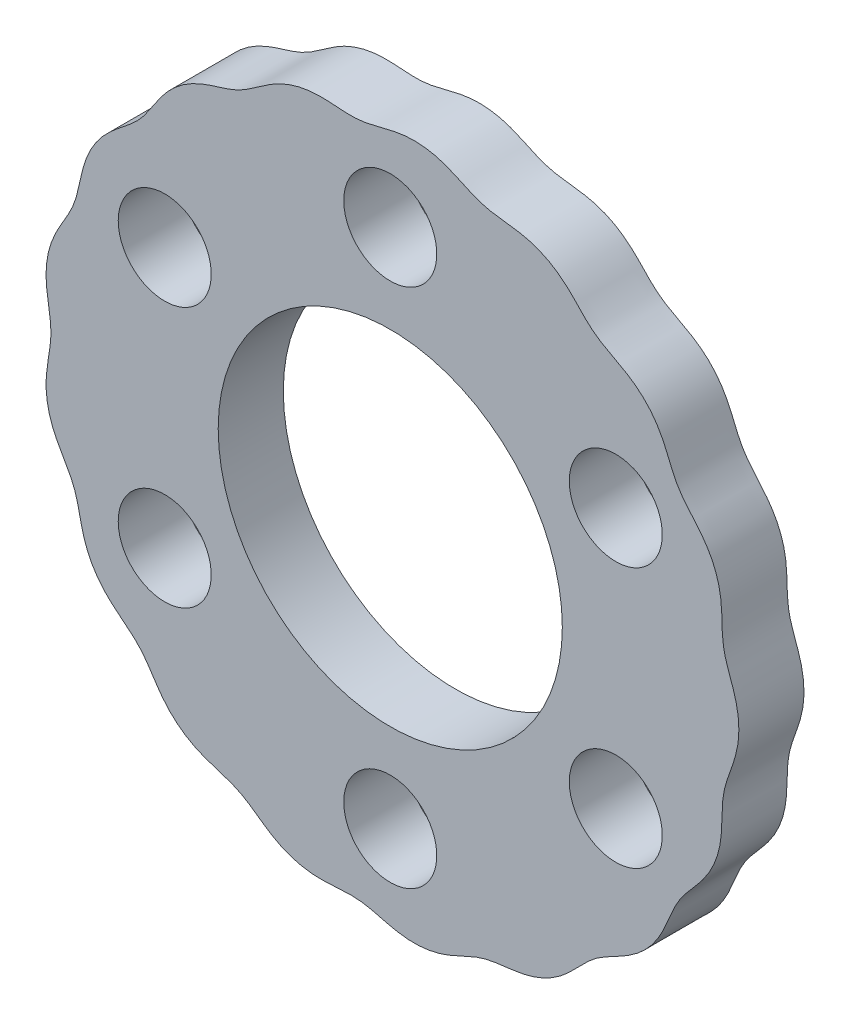
SolidWorks part; units mm, degrees
ref_plane "Front Plane" through (0, 0, 0) normal (0, 0, 1) x (1, 0, 0)
ref_plane "Top Plane" through (0, 0, 0) normal (0, 1, 0) x (1, 0, 0)
ref_plane "Right Plane" through (0, 0, 0) normal (1, 0, 0) x (0, 0, -1)
curve "Curve2"
  spline degree 3 poles (37.4783, -0.2259, 0) (37.4808, 0, 0) (37.4783, 0.2259, 0) (37.4707, 0.4525, 0) (37.4578, 0.6808, 0) (37.4392, 0.9112, 0) (37.4148, 1.1439, 0) (37.3841, 1.3792, 0) (37.347, 1.6168, 0) (37.3035, 1.8564, 0) (37.2536, 2.0975, 0) (37.1976, 2.3394, 0) (37.136, 2.5815, 0) (37.0693, 2.8232, 0) (36.9981, 3.0638, 0) (36.9231, 3.303, 0) (36.8453, 3.5401, 0) (36.7653, 3.7749, 0) (36.6841, 4.007, 0) (36.6025, 4.2364, 0) (36.5213, 4.463, 0) (36.4413, 4.6868, 0) (36.3632, 4.9078, 0) (36.2878, 5.1264, 0) (36.2156, 5.3428, 0) (36.1471, 5.5573, 0) (36.0829, 5.7702, 0) (36.0234, 5.9821, 0) (35.9687, 6.1933, 0) (35.9191, 6.4044, 0) (35.8748, 6.6158, 0) (35.8356, 6.8279, 0) (35.8015, 7.0413, 0) (35.7723, 7.2564, 0) (35.7478, 7.4735, 0) (35.7275, 7.693, 0) (35.7111, 7.9153, 0) (35.6979, 8.1406, 0) (35.6875, 8.369, 0) (35.6793, 8.6006, 0) (35.6724, 8.8355, 0) (35.6662, 9.0736, 0) (35.6601, 9.3147, 0) (35.6531, 9.5586, 0) (35.6447, 9.8048, 0) (35.634, 10.0529, 0) (35.6203, 10.3023, 0) (35.6031, 10.5525, 0) (35.5818, 10.8025, 0) (35.5559, 11.0518, 0) (35.525, 11.2995, 0) (35.4889, 11.5448, 0) (35.4474, 11.787, 0) (35.4005, 12.0254, 0) (35.3483, 12.2596, 0) (35.291, 12.4893, 0) (35.2289, 12.7144, 0) (35.1622, 12.9351, 0) (35.091, 13.152, 0) (35.0154, 13.3656, 0) (34.9354, 13.5768, 0) (34.8506, 13.7862, 0) (34.7607, 13.9947, 0) (34.6651, 14.2029, 0) (34.5635, 14.411, 0) (34.4554, 14.6192, 0) (34.3406, 14.8275, 0) (34.219, 15.0357, 0) (34.0907, 15.2432, 0) (33.956, 15.4497, 0) (33.8155, 15.6548, 0) (33.6697, 15.8579, 0) (33.5194, 16.0587, 0) (33.3655, 16.257, 0) (33.2088, 16.4524, 0) (33.0503, 16.6448, 0) (32.8908, 16.8344, 0) (32.7313, 17.021, 0) (32.5725, 17.205, 0) (32.4153, 17.3865, 0) (32.2603, 17.5659, 0) (32.1082, 17.7436, 0) (31.9595, 17.9199, 0) (31.8147, 18.0955, 0) (31.6742, 18.2708, 0) (31.5382, 18.4462, 0) (31.407, 18.6225, 0) (31.2806, 18.8, 0) (31.1589, 18.9792, 0) (31.042, 19.1607, 0) (30.9296, 19.3449, 0) (30.8215, 19.5321, 0) (30.7173, 19.7227, 0) (30.6165, 19.9169, 0) (30.5188, 20.115, 0) (30.4236, 20.3171, 0) (30.3303, 20.5231, 0) (30.2383, 20.733, 0) (30.1469, 20.9466, 0) (30.0556, 21.1638, 0) (29.9637, 21.3841, 0) (29.8706, 21.6072, 0) (29.7757, 21.8324, 0) (29.6784, 22.0591, 0) (29.5782, 22.2867, 0) (29.4748, 22.5143, 0) (29.3678, 22.7411, 0) (29.2569, 22.9663, 0) (29.1419, 23.1889, 0) (29.0229, 23.408, 0) (28.8999, 23.6228, 0) (28.7731, 23.8327, 0) (28.6426, 24.0371, 0) (28.5088, 24.2356, 0) (28.3719, 24.428, 0) (28.2321, 24.6144, 0) (28.0897, 24.7952, 0) (27.9445, 24.9709, 0) (27.7963, 25.142, 0) (27.6448, 25.3093, 0) (27.4893, 25.4735, 0) (27.3293, 25.635, 0) (27.164, 25.7942, 0) (26.9931, 25.9512, 0) (26.816, 26.1059, 0) (26.6325, 26.2582, 0) (26.4429, 26.4079, 0) (26.2472, 26.5545, 0) (26.0461, 26.6978, 0) (25.8402, 26.8376, 0) (25.6302, 26.9737, 0) (25.417, 27.106, 0) (25.2016, 27.2346, 0) (24.9847, 27.3596, 0) (24.7673, 27.4812, 0) (24.5503, 27.5998, 0) (24.3343, 27.7158, 0) (24.1202, 27.8297, 0) (23.9084, 27.9419, 0) (23.6997, 28.053, 0) (23.4943, 28.1637, 0) (23.2926, 28.2745, 0) (23.0949, 28.3861, 0) (22.9013, 28.4991, 0) (22.7119, 28.614, 0) (22.5265, 28.7314, 0) (22.3452, 28.8518, 0) (22.1677, 28.9756, 0) (21.9937, 29.1033, 0) (21.8229, 29.2352, 0) (21.6549, 29.3715, 0) (21.4892, 29.5124, 0) (21.3254, 29.658, 0) (21.163, 29.8082, 0) (21.0013, 29.963, 0) (20.8399, 30.1221, 0) (20.6781, 30.2853, 0) (20.5156, 30.4522, 0) (20.3517, 30.6222, 0) (20.1861, 30.7949, 0) (20.0183, 30.9695, 0) (19.848, 31.1454, 0) (19.6748, 31.3217, 0) (19.4987, 31.4976, 0) (19.3195, 31.6722, 0) (19.1372, 31.8446, 0) (18.9519, 32.0138, 0) (18.7639, 32.1791, 0) (18.5734, 32.3395, 0) (18.3807, 32.4944, 0) (18.1863, 32.6432, 0) (17.9906, 32.7855, 0) (17.794, 32.921, 0) (17.5967, 33.0498, 0) (17.399, 33.172, 0) (17.2008, 33.2881, 0) (17.0018, 33.3984, 0) (16.8015, 33.5036, 0) (16.5993, 33.6041, 0) (16.3945, 33.7003, 0) (16.1863, 33.7924, 0) (15.974, 33.8804, 0) (15.757, 33.9642, 0) (15.5351, 34.0438, 0) (15.3081, 34.1187, 0) (15.0764, 34.1889, 0) (14.8403, 34.2541, 0) (14.6003, 34.3142, 0) (14.3573, 34.3692, 0) (14.112, 34.4194, 0) (13.8652, 34.465, 0) (13.6178, 34.5064, 0) (13.3705, 34.544, 0) (13.1241, 34.5783, 0) (12.8791, 34.6101, 0) (12.6363, 34.64, 0) (12.3959, 34.6686, 0) (12.1585, 34.6967, 0) (11.9243, 34.725, 0) (11.6934, 34.7542, 0) (11.4659, 34.7851, 0) (11.2418, 34.8181, 0) (11.021, 34.8541, 0) (10.8034, 34.8934, 0) (10.5887, 34.9367, 0) (10.3766, 34.9842, 0) (10.1667, 35.0364, 0) (9.9586, 35.0935, 0) (9.7519, 35.1557, 0) (9.5461, 35.223, 0) (9.3408, 35.2955, 0) (9.1354, 35.3729, 0) (8.9295, 35.4551, 0) (8.7226, 35.5418, 0) (8.5143, 35.6326, 0) (8.3042, 35.7269, 0) (8.092, 35.8243, 0) (7.8773, 35.924, 0) (7.6601, 36.0254, 0) (7.44, 36.1277, 0) (7.2171, 36.2302, 0) (6.9915, 36.3318, 0) (6.7633, 36.4319, 0) (6.5327, 36.5295, 0) (6.3002, 36.6237, 0) (6.066, 36.7138, 0) (5.8308, 36.7991, 0) (5.5952, 36.8788, 0) (5.3596, 36.9526, 0) (5.1248, 37.0199, 0) (4.8911, 37.0807, 0) (4.6591, 37.1349, 0) (4.429, 37.1826, 0) (4.2008, 37.2241, 0) (3.9743, 37.2597, 0) (3.7491, 37.2898, 0) (3.5244, 37.3146, 0) (3.2995, 37.3344, 0) (3.0735, 37.3492, 0) (2.8457, 37.3589, 0) (2.6154, 37.3634, 0) (2.3823, 37.3622, 0) (2.1461, 37.3551, 0) (1.9069, 37.3419, 0) (1.665, 37.3225, 0) (1.4209, 37.2969, 0) (1.1753, 37.2652, 0) (0.9286, 37.2278, 0) (0.6818, 37.1851, 0) (0.4353, 37.1377, 0) (0.1899, 37.0862, 0) (-0.054, 37.0314, 0) (-0.2958, 36.974, 0) (-0.5352, 36.9149, 0) (-0.772, 36.8549, 0) (-1.0059, 36.7949, 0) (-1.237, 36.7355, 0) (-1.4651, 36.6776, 0) (-1.6905, 36.6218, 0) (-1.9134, 36.569, 0) (-2.1339, 36.5195, 0) (-2.3524, 36.474, 0) (-2.5692, 36.4329, 0) (-2.7849, 36.3965, 0) (-2.9998, 36.3651, 0) (-3.2143, 36.3389, 0) (-3.4291, 36.3179, 0) (-3.6444, 36.3021, 0) (-3.8608, 36.2914, 0) (-4.0788, 36.2857, 0) (-4.2986, 36.2845, 0) (-4.5207, 36.2874, 0) (-4.7454, 36.2942, 0) (-4.9729, 36.3041, 0) (-5.2035, 36.3165, 0) (-5.4371, 36.331, 0) (-5.6738, 36.3466, 0) (-5.9136, 36.3627, 0) (-6.1563, 36.3785, 0) (-6.4015, 36.3932, 0) (-6.649, 36.4062, 0) (-6.8982, 36.4165, 0) (-7.1486, 36.4236, 0) (-7.3996, 36.4267, 0) (-7.6504, 36.4253, 0) (-7.9003, 36.4189, 0) (-8.1485, 36.4072, 0) (-8.3943, 36.3899, 0) (-8.637, 36.3669, 0) (-8.8762, 36.3382, 0) (-9.1114, 36.3039, 0) (-9.3424, 36.2644, 0) (-9.5695, 36.2197, 0) (-9.793, 36.1703, 0) (-10.0134, 36.1161, 0) (-10.2316, 36.0573, 0) (-10.4482, 35.9936, 0) (-10.6642, 35.9249, 0) (-10.8802, 35.8507, 0) (-11.0966, 35.7705, 0) (-11.3137, 35.684, 0) (-11.5316, 35.5909, 0) (-11.7499, 35.491, 0) (-11.9684, 35.3844, 0) (-12.1867, 35.2712, 0) (-12.4042, 35.1519, 0) (-12.6204, 35.027, 0) (-12.8348, 34.8971, 0) (-13.0471, 34.7632, 0) (-13.2569, 34.626, 0) (-13.464, 34.4865, 0) (-13.6682, 34.3454, 0) (-13.8697, 34.2038, 0) (-14.0683, 34.0624, 0) (-14.2643, 33.9221, 0) (-14.4578, 33.7837, 0) (-14.6493, 33.6478, 0) (-14.8391, 33.515, 0) (-15.0276, 33.3859, 0) (-15.2152, 33.2608, 0) (-15.4025, 33.1403, 0) (-15.5899, 33.0244, 0) (-15.778, 32.9135, 0) (-15.9673, 32.8074, 0) (-16.1582, 32.7063, 0) (-16.3513, 32.61, 0) (-16.5469, 32.5183, 0) (-16.7454, 32.4309, 0) (-16.9471, 32.3475, 0) (-17.1523, 32.2675, 0) (-17.3611, 32.1906, 0) (-17.5737, 32.116, 0) (-17.7901, 32.0434, 0) (-18.0102, 31.9719, 0) (-18.2339, 31.901, 0) (-18.4609, 31.83, 0) (-18.6908, 31.7582, 0) (-18.9232, 31.685, 0) (-19.1575, 31.6097, 0) (-19.3931, 31.5319, 0) (-19.6292, 31.4509, 0) (-19.8652, 31.3664, 0) (-20.1001, 31.2779, 0) (-20.333, 31.1853, 0) (-20.5632, 31.0883, 0) (-20.7897, 30.9869, 0) (-21.0118, 30.8812, 0) (-21.229, 30.7714, 0) (-21.4406, 30.6575, 0) (-21.6465, 30.54, 0) (-21.8467, 30.419, 0) (-22.0414, 30.2948, 0) (-22.231, 30.1674, 0) (-22.4163, 30.0367, 0) (-22.5978, 29.9023, 0) (-22.7764, 29.764, 0) (-22.9526, 29.621, 0) (-23.1268, 29.4728, 0) (-23.2994, 29.3188, 0) (-23.4703, 29.1586, 0) (-23.6395, 28.992, 0) (-23.8066, 28.8188, 0) (-23.9715, 28.6393, 0) (-24.1336, 28.4539, 0) (-24.2927, 28.2632, 0) (-24.4486, 28.0679, 0) (-24.601, 27.8688, 0) (-24.75, 27.6668, 0) (-24.8955, 27.4628, 0) (-25.0376, 27.2577, 0) (-25.1766, 27.0524, 0) (-25.3127, 26.8478, 0) (-25.4465, 26.6445, 0) (-25.5782, 26.4433, 0) (-25.7085, 26.2448, 0) (-25.8378, 26.0494, 0) (-25.9668, 25.8577, 0) (-26.096, 25.67, 0) (-26.226, 25.4864, 0) (-26.3573, 25.307, 0) (-26.4907, 25.1321, 0) (-26.6264, 24.9614, 0) (-26.7652, 24.7949, 0) (-26.9073, 24.6323, 0) (-27.0533, 24.4734, 0) (-27.2032, 24.3178, 0) (-27.3575, 24.1651, 0) (-27.5163, 24.0148, 0) (-27.6795, 23.8664, 0) (-27.8473, 23.7194, 0) (-28.0193, 23.5732, 0) (-28.1956, 23.4273, 0) (-28.3757, 23.281, 0) (-28.5592, 23.1339, 0) (-28.7457, 22.9854, 0) (-28.9345, 22.8351, 0) (-29.125, 22.6824, 0) (-29.3164, 22.5271, 0) (-29.5079, 22.3689, 0) (-29.6987, 22.2075, 0) (-29.8878, 22.0429, 0) (-30.0743, 21.875, 0) (-30.2574, 21.7039, 0) (-30.4362, 21.5298, 0) (-30.6098, 21.353, 0) (-30.7777, 21.1738, 0) (-30.9394, 20.9925, 0) (-31.0944, 20.8097, 0) (-31.2428, 20.6255, 0) (-31.3846, 20.4402, 0) (-31.5202, 20.2539, 0) (-31.6501, 20.0663, 0) (-31.7747, 19.8772, 0) (-31.8947, 19.6859, 0) (-32.0105, 19.4918, 0) (-32.1225, 19.2942, 0) (-32.2308, 19.0922, 0) (-32.3354, 18.8854, 0) (-32.4363, 18.6734, 0) (-32.5331, 18.4559, 0) (-32.6256, 18.2331, 0) (-32.7136, 18.0054, 0) (-32.797, 17.7732, 0) (-32.8757, 17.5373, 0) (-32.9496, 17.2983, 0) (-33.0191, 17.0573, 0) (-33.0843, 16.815, 0) (-33.1456, 16.5722, 0) (-33.2035, 16.3297, 0) (-33.2584, 16.0883, 0) (-33.3111, 15.8486, 0) (-33.3622, 15.6112, 0) (-33.4122, 15.3765, 0) (-33.462, 15.1449, 0) (-33.5121, 14.9167, 0) (-33.5634, 14.6919, 0) (-33.6163, 14.4708, 0) (-33.6717, 14.2533, 0) (-33.73, 14.0392, 0) (-33.7917, 13.8285, 0) (-33.8574, 13.6208, 0) (-33.9274, 13.4159, 0) (-34.0021, 13.2133, 0) (-34.0816, 13.0127, 0) (-34.1662, 12.8137, 0) (-34.2557, 12.6157, 0) (-34.3503, 12.4183, 0) (-34.4498, 12.2209, 0) (-34.5539, 12.0231, 0) (-34.6623, 11.8244, 0) (-34.7746, 11.6244, 0) (-34.8902, 11.4227, 0) (-35.0087, 11.2188, 0) (-35.1292, 11.0125, 0) (-35.2511, 10.8037, 0) (-35.3737, 10.592, 0) (-35.496, 10.3776, 0) (-35.6171, 10.1604, 0) (-35.7363, 9.9405, 0) (-35.8526, 9.7183, 0) (-35.9652, 9.494, 0) (-36.0733, 9.268, 0) (-36.1761, 9.041, 0) (-36.2731, 8.8133, 0) (-36.3637, 8.5856, 0) (-36.4478, 8.3583, 0) (-36.5252, 8.132, 0) (-36.5958, 7.9069, 0) (-36.66, 7.6831, 0) (-36.7181, 7.4605, 0) (-36.7704, 7.2389, 0) (-36.8174, 7.0175, 0) (-36.8593, 6.7956, 0) (-36.8963, 6.5725, 0) (-36.9285, 6.3474, 0) (-36.9556, 6.1194, 0) (-36.9776, 5.8882, 0) (-36.994, 5.6534, 0) (-37.0047, 5.415, 0) (-37.0094, 5.1733, 0) (-37.0082, 4.9286, 0) (-37.001, 4.6816, 0) (-36.9882, 4.433, 0) (-36.9699, 4.1834, 0) (-36.9468, 3.9335, 0) (-36.9193, 3.6841, 0) (-36.8882, 3.4358, 0) (-36.8541, 3.1891, 0) (-36.8178, 2.9446, 0) (-36.7802, 2.7025, 0) (-36.7419, 2.4632, 0) (-36.7039, 2.2268, 0) (-36.6669, 1.9934, 0) (-36.6316, 1.7629, 0) (-36.5986, 1.5354, 0) (-36.5687, 1.3105, 0) (-36.5424, 1.0881, 0) (-36.5202, 0.8678, 0) (-36.5025, 0.6492, 0) (-36.4896, 0.4321, 0) (-36.4818, 0.2158, 0) (-36.4791, 0, 0) (-36.4818, -0.2158, 0) (-36.4896, -0.4321, 0) (-36.5025, -0.6492, 0) (-36.5202, -0.8678, 0) (-36.5424, -1.0881, 0) (-36.5687, -1.3105, 0) (-36.5986, -1.5354, 0) (-36.6316, -1.7629, 0) (-36.6669, -1.9934, 0) (-36.7039, -2.2268, 0) (-36.7419, -2.4632, 0) (-36.7802, -2.7025, 0) (-36.8178, -2.9446, 0) (-36.8541, -3.1891, 0) (-36.8882, -3.4358, 0) (-36.9193, -3.6841, 0) (-36.9468, -3.9335, 0) (-36.9699, -4.1834, 0) (-36.9882, -4.433, 0) (-37.001, -4.6816, 0) (-37.0082, -4.9286, 0) (-37.0094, -5.1733, 0) (-37.0047, -5.415, 0) (-36.994, -5.6534, 0) (-36.9776, -5.8882, 0) (-36.9556, -6.1194, 0) (-36.9285, -6.3474, 0) (-36.8963, -6.5725, 0) (-36.8593, -6.7956, 0) (-36.8174, -7.0175, 0) (-36.7704, -7.2389, 0) (-36.7181, -7.4605, 0) (-36.66, -7.6831, 0) (-36.5958, -7.9069, 0) (-36.5252, -8.132, 0) (-36.4478, -8.3583, 0) (-36.3637, -8.5856, 0) (-36.2731, -8.8133, 0) (-36.1761, -9.041, 0) (-36.0733, -9.268, 0) (-35.9652, -9.494, 0) (-35.8526, -9.7183, 0) (-35.7363, -9.9405, 0) (-35.6171, -10.1604, 0) (-35.496, -10.3776, 0) (-35.3737, -10.592, 0) (-35.2511, -10.8037, 0) (-35.1292, -11.0125, 0) (-35.0087, -11.2188, 0) (-34.8902, -11.4227, 0) (-34.7746, -11.6244, 0) (-34.6623, -11.8244, 0) (-34.5539, -12.0231, 0) (-34.4498, -12.2209, 0) (-34.3503, -12.4183, 0) (-34.2557, -12.6157, 0) (-34.1662, -12.8137, 0) (-34.0816, -13.0127, 0) (-34.0021, -13.2133, 0) (-33.9274, -13.4159, 0) (-33.8574, -13.6208, 0) (-33.7917, -13.8285, 0) (-33.73, -14.0392, 0) (-33.6717, -14.2533, 0) (-33.6163, -14.4708, 0) (-33.5634, -14.6919, 0) (-33.5121, -14.9167, 0) (-33.462, -15.1449, 0) (-33.4122, -15.3765, 0) (-33.3622, -15.6112, 0) (-33.3111, -15.8486, 0) (-33.2584, -16.0883, 0) (-33.2035, -16.3297, 0) (-33.1456, -16.5722, 0) (-33.0843, -16.815, 0) (-33.0191, -17.0573, 0) (-32.9496, -17.2983, 0) (-32.8757, -17.5373, 0) (-32.797, -17.7732, 0) (-32.7136, -18.0054, 0) (-32.6256, -18.2331, 0) (-32.5331, -18.4559, 0) (-32.4363, -18.6734, 0) (-32.3354, -18.8854, 0) (-32.2308, -19.0922, 0) (-32.1225, -19.2942, 0) (-32.0105, -19.4918, 0) (-31.8947, -19.6859, 0) (-31.7747, -19.8772, 0) (-31.6501, -20.0663, 0) (-31.5202, -20.2539, 0) (-31.3846, -20.4402, 0) (-31.2428, -20.6255, 0) (-31.0944, -20.8097, 0) (-30.9394, -20.9925, 0) (-30.7777, -21.1738, 0) (-30.6098, -21.353, 0) (-30.4362, -21.5298, 0) (-30.2574, -21.7039, 0) (-30.0743, -21.875, 0) (-29.8878, -22.0429, 0) (-29.6987, -22.2075, 0) (-29.5079, -22.3689, 0) (-29.3164, -22.5271, 0) (-29.125, -22.6824, 0) (-28.9345, -22.8351, 0) (-28.7457, -22.9854, 0) (-28.5592, -23.1339, 0) (-28.3757, -23.281, 0) (-28.1956, -23.4273, 0) (-28.0193, -23.5732, 0) (-27.8473, -23.7194, 0) (-27.6795, -23.8664, 0) (-27.5163, -24.0148, 0) (-27.3575, -24.1651, 0) (-27.2032, -24.3178, 0) (-27.0533, -24.4734, 0) (-26.9073, -24.6323, 0) (-26.7652, -24.7949, 0) (-26.6264, -24.9614, 0) (-26.4907, -25.1321, 0) (-26.3573, -25.307, 0) (-26.226, -25.4864, 0) (-26.096, -25.67, 0) (-25.9668, -25.8577, 0) (-25.8378, -26.0494, 0) (-25.7085, -26.2448, 0) (-25.5782, -26.4433, 0) (-25.4465, -26.6445, 0) (-25.3127, -26.8478, 0) (-25.1766, -27.0524, 0) (-25.0376, -27.2577, 0) (-24.8955, -27.4628, 0) (-24.75, -27.6668, 0) (-24.601, -27.8688, 0) (-24.4486, -28.0679, 0) (-24.2927, -28.2632, 0) (-24.1336, -28.4539, 0) (-23.9715, -28.6393, 0) (-23.8066, -28.8188, 0) (-23.6395, -28.992, 0) (-23.4703, -29.1586, 0) (-23.2994, -29.3188, 0) (-23.1268, -29.4728, 0) (-22.9526, -29.621, 0) (-22.7764, -29.764, 0) (-22.5978, -29.9023, 0) (-22.4163, -30.0367, 0) (-22.231, -30.1674, 0) (-22.0414, -30.2948, 0) (-21.8467, -30.419, 0) (-21.6465, -30.54, 0) (-21.4406, -30.6575, 0) (-21.229, -30.7714, 0) (-21.0118, -30.8812, 0) (-20.7897, -30.9869, 0) (-20.5632, -31.0883, 0) (-20.333, -31.1853, 0) (-20.1001, -31.2779, 0) (-19.8652, -31.3664, 0) (-19.6292, -31.4509, 0) (-19.3931, -31.5319, 0) (-19.1575, -31.6097, 0) (-18.9232, -31.685, 0) (-18.6908, -31.7582, 0) (-18.4609, -31.83, 0) (-18.2339, -31.901, 0) (-18.0102, -31.9719, 0) (-17.7901, -32.0434, 0) (-17.5737, -32.116, 0) (-17.3611, -32.1906, 0) (-17.1523, -32.2675, 0) (-16.9471, -32.3475, 0) (-16.7454, -32.4309, 0) (-16.5469, -32.5183, 0) (-16.3513, -32.61, 0) (-16.1582, -32.7063, 0) (-15.9673, -32.8074, 0) (-15.778, -32.9135, 0) (-15.5899, -33.0244, 0) (-15.4025, -33.1403, 0) (-15.2152, -33.2608, 0) (-15.0276, -33.3859, 0) (-14.8391, -33.515, 0) (-14.6493, -33.6478, 0) (-14.4578, -33.7837, 0) (-14.2643, -33.9221, 0) (-14.0683, -34.0624, 0) (-13.8697, -34.2038, 0) (-13.6682, -34.3454, 0) (-13.464, -34.4865, 0) (-13.2569, -34.626, 0) (-13.0471, -34.7632, 0) (-12.8348, -34.8971, 0) (-12.6204, -35.027, 0) (-12.4042, -35.1519, 0) (-12.1867, -35.2712, 0) (-11.9684, -35.3844, 0) (-11.7499, -35.491, 0) (-11.5316, -35.5909, 0) (-11.3137, -35.684, 0) (-11.0966, -35.7705, 0) (-10.8802, -35.8507, 0) (-10.6642, -35.9249, 0) (-10.4482, -35.9936, 0) (-10.2316, -36.0573, 0) (-10.0134, -36.1161, 0) (-9.793, -36.1703, 0) (-9.5695, -36.2197, 0) (-9.3424, -36.2644, 0) (-9.1114, -36.3039, 0) (-8.8762, -36.3382, 0) (-8.637, -36.3669, 0) (-8.3943, -36.3899, 0) (-8.1485, -36.4072, 0) (-7.9003, -36.4189, 0) (-7.6504, -36.4253, 0) (-7.3996, -36.4267, 0) (-7.1486, -36.4236, 0) (-6.8982, -36.4165, 0) (-6.649, -36.4062, 0) (-6.4015, -36.3932, 0) (-6.1563, -36.3785, 0) (-5.9136, -36.3627, 0) (-5.6738, -36.3466, 0) (-5.4371, -36.331, 0) (-5.2035, -36.3165, 0) (-4.9729, -36.3041, 0) (-4.7454, -36.2942, 0) (-4.5207, -36.2874, 0) (-4.2986, -36.2845, 0) (-4.0788, -36.2857, 0) (-3.8608, -36.2914, 0) (-3.6444, -36.3021, 0) (-3.4291, -36.3179, 0) (-3.2143, -36.3389, 0) (-2.9998, -36.3651, 0) (-2.7849, -36.3965, 0) (-2.5692, -36.4329, 0) (-2.3524, -36.474, 0) (-2.1339, -36.5195, 0) (-1.9134, -36.569, 0) (-1.6905, -36.6218, 0) (-1.4651, -36.6776, 0) (-1.237, -36.7355, 0) (-1.0059, -36.7949, 0) (-0.772, -36.8549, 0) (-0.5352, -36.9149, 0) (-0.2958, -36.974, 0) (-0.054, -37.0314, 0) (0.1899, -37.0862, 0) (0.4353, -37.1377, 0) (0.6818, -37.1851, 0) (0.9286, -37.2278, 0) (1.1753, -37.2652, 0) (1.4209, -37.2969, 0) (1.665, -37.3225, 0) (1.9069, -37.3419, 0) (2.1461, -37.3551, 0) (2.3823, -37.3622, 0) (2.6154, -37.3634, 0) (2.8457, -37.3589, 0) (3.0735, -37.3492, 0) (3.2995, -37.3344, 0) (3.5244, -37.3146, 0) (3.7491, -37.2898, 0) (3.9743, -37.2597, 0) (4.2008, -37.2241, 0) (4.429, -37.1826, 0) (4.6591, -37.1349, 0) (4.8911, -37.0807, 0) (5.1248, -37.0199, 0) (5.3596, -36.9526, 0) (5.5952, -36.8788, 0) (5.8308, -36.7991, 0) (6.066, -36.7138, 0) (6.3002, -36.6237, 0) (6.5327, -36.5295, 0) (6.7633, -36.4319, 0) (6.9915, -36.3318, 0) (7.2171, -36.2302, 0) (7.44, -36.1277, 0) (7.6601, -36.0254, 0) (7.8773, -35.924, 0) (8.092, -35.8243, 0) (8.3042, -35.7269, 0) (8.5143, -35.6326, 0) (8.7226, -35.5418, 0) (8.9295, -35.4551, 0) (9.1354, -35.3729, 0) (9.3408, -35.2955, 0) (9.5461, -35.223, 0) (9.7519, -35.1557, 0) (9.9586, -35.0935, 0) (10.1667, -35.0364, 0) (10.3766, -34.9842, 0) (10.5887, -34.9367, 0) (10.8034, -34.8934, 0) (11.021, -34.8541, 0) (11.2418, -34.8181, 0) (11.4659, -34.7851, 0) (11.6934, -34.7542, 0) (11.9243, -34.725, 0) (12.1585, -34.6967, 0) (12.3959, -34.6686, 0) (12.6363, -34.64, 0) (12.8791, -34.6101, 0) (13.1241, -34.5783, 0) (13.3705, -34.544, 0) (13.6178, -34.5064, 0) (13.8652, -34.465, 0) (14.112, -34.4194, 0) (14.3573, -34.3692, 0) (14.6003, -34.3142, 0) (14.8403, -34.2541, 0) (15.0764, -34.1889, 0) (15.3081, -34.1187, 0) (15.5351, -34.0438, 0) (15.757, -33.9642, 0) (15.974, -33.8804, 0) (16.1863, -33.7924, 0) (16.3945, -33.7003, 0) (16.5993, -33.6041, 0) (16.8015, -33.5036, 0) (17.0018, -33.3984, 0) (17.2008, -33.2881, 0) (17.399, -33.172, 0) (17.5967, -33.0498, 0) (17.794, -32.921, 0) (17.9906, -32.7855, 0) (18.1863, -32.6432, 0) (18.3807, -32.4944, 0) (18.5734, -32.3395, 0) (18.7639, -32.1791, 0) (18.9519, -32.0138, 0) (19.1372, -31.8446, 0) (19.3195, -31.6722, 0) (19.4987, -31.4976, 0) (19.6748, -31.3217, 0) (19.848, -31.1454, 0) (20.0183, -30.9695, 0) (20.1861, -30.7949, 0) (20.3517, -30.6222, 0) (20.5156, -30.4522, 0) (20.6781, -30.2853, 0) (20.8399, -30.1221, 0) (21.0013, -29.963, 0) (21.163, -29.8082, 0) (21.3254, -29.658, 0) (21.4892, -29.5124, 0) (21.6549, -29.3715, 0) (21.8229, -29.2352, 0) (21.9937, -29.1033, 0) (22.1677, -28.9756, 0) (22.3452, -28.8518, 0) (22.5265, -28.7314, 0) (22.7119, -28.614, 0) (22.9013, -28.4991, 0) (23.0949, -28.3861, 0) (23.2926, -28.2745, 0) (23.4943, -28.1637, 0) (23.6997, -28.053, 0) (23.9084, -27.9419, 0) (24.1202, -27.8297, 0) (24.3343, -27.7158, 0) (24.5503, -27.5998, 0) (24.7673, -27.4812, 0) (24.9847, -27.3596, 0) (25.2016, -27.2346, 0) (25.417, -27.106, 0) (25.6302, -26.9737, 0) (25.8402, -26.8376, 0) (26.0461, -26.6978, 0) (26.2472, -26.5545, 0) (26.4429, -26.4079, 0) (26.6325, -26.2582, 0) (26.816, -26.1059, 0) (26.9931, -25.9512, 0) (27.164, -25.7942, 0) (27.3293, -25.635, 0) (27.4893, -25.4735, 0) (27.6448, -25.3093, 0) (27.7963, -25.142, 0) (27.9445, -24.9709, 0) (28.0897, -24.7952, 0) (28.2321, -24.6144, 0) (28.3719, -24.428, 0) (28.5088, -24.2356, 0) (28.6426, -24.0371, 0) (28.7731, -23.8327, 0) (28.8999, -23.6228, 0) (29.0229, -23.408, 0) (29.1419, -23.1889, 0) (29.2569, -22.9663, 0) (29.3678, -22.7411, 0) (29.4748, -22.5143, 0) (29.5782, -22.2867, 0) (29.6784, -22.0591, 0) (29.7757, -21.8324, 0) (29.8706, -21.6072, 0) (29.9637, -21.3841, 0) (30.0556, -21.1638, 0) (30.1469, -20.9466, 0) (30.2383, -20.733, 0) (30.3303, -20.5231, 0) (30.4236, -20.3171, 0) (30.5188, -20.115, 0) (30.6165, -19.9169, 0) (30.7173, -19.7227, 0) (30.8215, -19.5321, 0) (30.9296, -19.3449, 0) (31.042, -19.1607, 0) (31.1589, -18.9792, 0) (31.2806, -18.8, 0) (31.407, -18.6225, 0) (31.5382, -18.4462, 0) (31.6742, -18.2708, 0) (31.8147, -18.0955, 0) (31.9595, -17.9199, 0) (32.1082, -17.7436, 0) (32.2603, -17.5659, 0) (32.4153, -17.3865, 0) (32.5725, -17.205, 0) (32.7313, -17.021, 0) (32.8908, -16.8344, 0) (33.0503, -16.6448, 0) (33.2088, -16.4524, 0) (33.3655, -16.257, 0) (33.5194, -16.0587, 0) (33.6697, -15.8579, 0) (33.8155, -15.6548, 0) (33.956, -15.4497, 0) (34.0907, -15.2432, 0) (34.219, -15.0357, 0) (34.3406, -14.8275, 0) (34.4554, -14.6192, 0) (34.5635, -14.411, 0) (34.6651, -14.2029, 0) (34.7607, -13.9947, 0) (34.8506, -13.7862, 0) (34.9354, -13.5768, 0) (35.0154, -13.3656, 0) (35.091, -13.152, 0) (35.1622, -12.9351, 0) (35.2289, -12.7144, 0) (35.291, -12.4893, 0) (35.3483, -12.2596, 0) (35.4005, -12.0254, 0) (35.4474, -11.787, 0) (35.4889, -11.5448, 0) (35.525, -11.2995, 0) (35.5559, -11.0518, 0) (35.5818, -10.8025, 0) (35.6031, -10.5525, 0) (35.6203, -10.3023, 0) (35.634, -10.0529, 0) (35.6447, -9.8048, 0) (35.6531, -9.5586, 0) (35.6601, -9.3147, 0) (35.6662, -9.0736, 0) (35.6724, -8.8355, 0) (35.6793, -8.6006, 0) (35.6875, -8.369, 0) (35.6979, -8.1406, 0) (35.7111, -7.9153, 0) (35.7275, -7.693, 0) (35.7478, -7.4735, 0) (35.7723, -7.2564, 0) (35.8015, -7.0413, 0) (35.8356, -6.8279, 0) (35.8748, -6.6158, 0) (35.9191, -6.4044, 0) (35.9687, -6.1933, 0) (36.0234, -5.9821, 0) (36.0829, -5.7702, 0) (36.1471, -5.5573, 0) (36.2156, -5.3428, 0) (36.2878, -5.1264, 0) (36.3632, -4.9078, 0) (36.4413, -4.6868, 0) (36.5213, -4.463, 0) (36.6025, -4.2364, 0) (36.6841, -4.007, 0) (36.7653, -3.7749, 0) (36.8453, -3.5401, 0) (36.9231, -3.303, 0) (36.9981, -3.0638, 0) (37.0693, -2.8232, 0) (37.136, -2.5815, 0) (37.1976, -2.3394, 0) (37.2536, -2.0975, 0) (37.3035, -1.8564, 0) (37.347, -1.6168, 0) (37.3841, -1.3792, 0) (37.4148, -1.1439, 0) (37.4392, -0.9112, 0) (37.4578, -0.6808, 0) (37.4707, -0.4525, 0) (37.4783, -0.2259, 0) (37.4808, 0, 0) (37.4783, 0.2259, 0) knots -0.002887 -0.001918 -0.000957 0 0.000957 0.001918 0.002887 0.003867 0.00486 0.005867 0.006888 0.007922 0.008967 0.010021 0.011082 0.012147 0.013213 0.014278 0.015338 0.016391 0.017435 0.018469 0.019491 0.020499 0.021494 0.022476 0.023443 0.024398 0.025342 0.026275 0.0272 0.02812 0.029035 0.02995 0.030866 0.031786 0.032712 0.033647 0.034593 0.03555 0.03652 0.037504 0.038501 0.039512 0.040536 0.041572 0.042618 0.043672 0.044733 0.045798 0.046864 0.047929 0.048989 0.050042 0.051085 0.052117 0.053135 0.054139 0.05513 0.056108 0.057075 0.058036 0.058992 0.05995 0.060912 0.061883 0.062865 0.063861 0.06487 0.065893 0.066929 0.067976 0.069032 0.070094 0.071159 0.072225 0.073289 0.074348 0.0754 0.076442 0.077474 0.078493 0.0795 0.080492 0.081471 0.082436 0.083389 0.084331 0.085262 0.086186 0.087105 0.08802 0.088935 0.089851 0.090772 0.0917 0.092637 0.093584 0.094544 0.095516 0.096502 0.097502 0.098515 0.099541 0.100579 0.101627 0.102683 0.103745 0.10481 0.105876 0.10694 0.107999 0.10905 0.110092 0.111121 0.112137 0.113139 0.114127 0.115103 0.116069 0.117028 0.117985 0.118943 0.119906 0.120879 0.121863 0.122861 0.123873 0.124898 0.125937 0.126985 0.128042 0.129105 0.130171 0.131236 0.1323 0.133357 0.134408 0.135449 0.136478 0.137495 0.138499 0.139489 0.140466 0.141429 0.14238 0.143319 0.14425 0.145172 0.14609 0.147005 0.14792 0.148837 0.149759 0.150688 0.151627 0.152576 0.153538 0.154513 0.155501 0.156503 0.157519 0.158547 0.159587 0.160636 0.161693 0.162756 0.163821 0.164887 0.165951 0.167008 0.168058 0.169098 0.170125 0.171138 0.172138 0.173123 0.174097 0.175062 0.17602 0.176977 0.177936 0.178901 0.179875 0.180862 0.181862 0.182877 0.183904 0.184944 0.185995 0.187053 0.188117 0.189182 0.190248 0.19131 0.192367 0.193416 0.194455 0.195482 0.196497 0.197499 0.198486 0.19946 0.200421 0.20137 0.202308 0.203236 0.204158 0.205075 0.20599 0.206905 0.207823 0.208746 0.209677 0.210617 0.211569 0.212532 0.21351 0.214501 0.215505 0.216523 0.217554 0.218595 0.219646 0.220704 0.221767 0.222833 0.223899 0.224961 0.226018 0.227066 0.228103 0.229128 0.230139 0.231136 0.23212 0.233092 0.234055 0.235013 0.235969 0.236929 0.237896 0.238872 0.239861 0.240864 0.24188 0.242911 0.243953 0.245005 0.246064 0.247128 0.248194 0.249259 0.250321 0.251376 0.252423 0.25346 0.254486 0.255498 0.256497 0.257483 0.258454 0.259413 0.26036 0.261296 0.262223 0.263144 0.26406 0.264975 0.26589 0.266809 0.267733 0.268666 0.269608 0.270561 0.271527 0.272507 0.2735 0.274507 0.275528 0.27656 0.277603 0.278656 0.279715 0.280779 0.281845 0.28291 0.283972 0.285027 0.286073 0.287109 0.288131 0.28914 0.290134 0.291116 0.292086 0.293048 0.294005 0.294962 0.295923 0.296891 0.297869 0.29886 0.299866 0.300885 0.301917 0.302961 0.304015 0.305075 0.30614 0.307206 0.30827 0.309331 0.310385 0.311431 0.312466 0.313489 0.314499 0.315496 0.316479 0.317448 0.318404 0.319349 0.320283 0.321209 0.322129 0.323045 0.32396 0.324876 0.325795 0.326721 0.327655 0.328599 0.329554 0.330523 0.331505 0.332501 0.33351 0.334533 0.335567 0.336612 0.337666 0.338726 0.33979 0.340856 0.341921 0.342982 0.344036 0.345081 0.346114 0.347134 0.34814 0.349132 0.350111 0.35108 0.35204 0.352997 0.353955 0.354916 0.355886 0.356867 0.35786 0.358868 0.35989 0.360924 0.36197 0.363025 0.364086 0.365151 0.366217 0.367281 0.368341 0.369394 0.370438 0.371471 0.372492 0.3735 0.374494 0.375474 0.376441 0.377395 0.378338 0.379271 0.380196 0.381115 0.38203 0.382945 0.383861 0.384781 0.385708 0.386644 0.38759 0.388548 0.389519 0.390503 0.391501 0.392513 0.393538 0.394574 0.395621 0.396676 0.397737 0.398802 0.399868 0.400932 0.401992 0.403045 0.404087 0.405118 0.406136 0.407139 0.408129 0.409106 0.410073 0.411033 0.41199 0.412947 0.41391 0.414882 0.415865 0.416861 0.417871 0.418895 0.419931 0.420979 0.422035 0.423098 0.424163 0.425229 0.426292 0.427351 0.428402 0.429444 0.430475 0.431494 0.4325 0.433491 0.434469 0.435434 0.436386 0.437327 0.438258 0.439182 0.4401 0.441015 0.44193 0.442847 0.443768 0.444696 0.445634 0.446582 0.447542 0.448515 0.449502 0.450502 0.451517 0.452543 0.453582 0.45463 0.455686 0.456748 0.457814 0.45888 0.459943 0.461002 0.462053 0.463094 0.464122 0.465137 0.466138 0.467126 0.468101 0.469066 0.470026 0.470982 0.47194 0.472904 0.473878 0.474863 0.475861 0.476874 0.4779 0.478939 0.479988 0.481046 0.482109 0.483175 0.48424 0.485303 0.486361 0.48741 0.488451 0.48948 0.490496 0.491499 0.492488 0.493464 0.494426 0.495376 0.496315 0.497245 0.498168 0.499085 0.5 0.500915 0.501832 0.502755 0.503685 0.504624 0.505574 0.506536 0.507512 0.508501 0.509504 0.51052 0.511549 0.51259 0.513639 0.514697 0.51576 0.516825 0.517891 0.518954 0.520012 0.521061 0.5221 0.523126 0.524139 0.525137 0.526122 0.527096 0.52806 0.529018 0.529974 0.530934 0.531899 0.532874 0.533862 0.534863 0.535878 0.536906 0.537947 0.538998 0.540057 0.54112 0.542186 0.543252 0.544314 0.54537 0.546418 0.547457 0.548483 0.549498 0.550498 0.551485 0.552458 0.553418 0.554366 0.555304 0.556232 0.557153 0.55807 0.558985 0.5599 0.560818 0.561742 0.562673 0.563614 0.564566 0.565531 0.566509 0.5675 0.568506 0.569525 0.570556 0.571598 0.572649 0.573708 0.574771 0.575837 0.576902 0.577965 0.579021 0.580069 0.581105 0.582129 0.583139 0.584135 0.585118 0.58609 0.587053 0.58801 0.588967 0.589927 0.590894 0.591871 0.592861 0.593864 0.594882 0.595913 0.596955 0.598008 0.599068 0.600132 0.601198 0.602263 0.603324 0.604379 0.605426 0.606462 0.607487 0.608499 0.609497 0.610481 0.611452 0.61241 0.613356 0.614292 0.615219 0.616139 0.617055 0.61797 0.618885 0.619804 0.620729 0.621662 0.622605 0.623559 0.624526 0.625506 0.6265 0.627508 0.628529 0.629562 0.630606 0.631659 0.632719 0.633783 0.634849 0.635914 0.636975 0.63803 0.639076 0.64011 0.641132 0.64214 0.643133 0.644114 0.645084 0.646045 0.647003 0.64796 0.64892 0.649889 0.650868 0.65186 0.652866 0.653886 0.654919 0.655964 0.657018 0.658079 0.659144 0.66021 0.661274 0.662334 0.663388 0.664433 0.665467 0.66649 0.667499 0.668495 0.669477 0.670446 0.671401 0.672345 0.673279 0.674205 0.675124 0.67604 0.676955 0.677871 0.678791 0.679717 0.680651 0.681596 0.682552 0.683521 0.684504 0.685501 0.686511 0.687534 0.688569 0.689615 0.690669 0.69173 0.692794 0.69386 0.694925 0.695985 0.697039 0.698083 0.699115 0.700134 0.70114 0.702131 0.703109 0.704077 0.705038 0.705995 0.706952 0.707914 0.708884 0.709866 0.71086 0.711869 0.712891 0.713927 0.714973 0.716028 0.71709 0.718155 0.719221 0.720285 0.721344 0.722397 0.72344 0.724472 0.725493 0.7265 0.727493 0.728473 0.729439 0.730392 0.731334 0.732267 0.733191 0.73411 0.735025 0.73594 0.736856 0.737777 0.738704 0.73964 0.740587 0.741546 0.742517 0.743503 0.744502 0.745514 0.74654 0.747577 0.748624 0.749679 0.750741 0.751806 0.752872 0.753936 0.754995 0.756047 0.757089 0.75812 0.759136 0.760139 0.761128 0.762104 0.763071 0.764031 0.764987 0.765945 0.766908 0.76788 0.768864 0.769861 0.770872 0.771897 0.772934 0.773982 0.775039 0.776101 0.777167 0.778233 0.779296 0.780354 0.781405 0.782446 0.783477 0.784495 0.785499 0.78649 0.787468 0.788431 0.789383 0.790323 0.791254 0.792177 0.793095 0.79401 0.794925 0.795842 0.796764 0.797692 0.79863 0.799579 0.80054 0.801514 0.802501 0.803503 0.804518 0.805545 0.806584 0.807633 0.80869 0.809752 0.810818 0.811883 0.812947 0.814005 0.815056 0.816096 0.817123 0.818138 0.819138 0.820125 0.821099 0.822064 0.823023 0.82398 0.824938 0.825903 0.826877 0.827862 0.828862 0.829875 0.830902 0.831942 0.832992 0.834049 0.835113 0.836179 0.837244 0.838307 0.839364 0.840413 0.841453 0.842481 0.843497 0.844499 0.845487 0.846462 0.847424 0.848373 0.849312 0.850241 0.851163 0.85208 0.852995 0.85391 0.854828 0.85575 0.856681 0.85762 0.858571 0.859534 0.860511 0.861501 0.862505 0.863522 0.864551 0.865592 0.866643 0.8677 0.868764 0.869829 0.870895 0.871958 0.873015 0.874063 0.875102 0.876127 0.877139 0.878137 0.879121 0.880094 0.881057 0.882015 0.882972 0.883931 0.884897 0.885873 0.886861 0.887863 0.888879 0.889908 0.89095 0.892001 0.89306 0.894124 0.89519 0.896255 0.897317 0.898373 0.899421 0.900459 0.901485 0.902498 0.903498 0.904484 0.905456 0.906416 0.907363 0.9083 0.909228 0.910149 0.911065 0.91198 0.912895 0.913814 0.914738 0.915669 0.916611 0.917564 0.918529 0.919508 0.9205 0.921507 0.922526 0.923558 0.9246 0.925652 0.926711 0.927775 0.928841 0.929906 0.930968 0.932024 0.933071 0.934107 0.93513 0.936139 0.937135 0.938117 0.939088 0.94005 0.941008 0.941964 0.942925 0.943892 0.94487 0.945861 0.946865 0.947883 0.948915 0.949958 0.951011 0.952071 0.953136 0.954202 0.955267 0.956328 0.957382 0.958428 0.959464 0.960488 0.961499 0.962496 0.96348 0.96445 0.965407 0.966353 0.967288 0.968214 0.969134 0.97005 0.970965 0.97188 0.9728 0.973725 0.974658 0.975602 0.976557 0.977524 0.978506 0.979501 0.980509 0.981531 0.982565 0.983609 0.984662 0.985722 0.986787 0.987853 0.988918 0.989979 0.991033 0.992078 0.993112 0.994133 0.99514 0.996133 0.997113 0.998082 0.999043 1 1.000957 1.001918 1.002887 periodic
sketch "Sketch2" plane through (0, 0, 0) normal (0, 0, 1) x (1, 0, 0)
  spline S0 degree 3 number of poles 1003 (37.48, 0) -> (37.48, 0) construction
  spline S1 degree 3 number of poles 1003 (37.48, 0) -> (37.48, 0)
extrude "Boss-Extrude1" add sketch "Sketch2" along normal blind 7
sketch "Sketch5" plane through (0, 0, 0) normal (0, 0, -1) x (-1, 0, 0)
  circle A0 centre (0, 0) radius 18.5
  dimension "D1" = 37
extrude "Cut-Extrude2" cut sketch "Sketch5" against normal up to next
sketch "Sketch6" plane through (0, 0, 0) normal (0, 0, -1) x (-1, 0, 0)
  circle A0 centre (0, 0) radius 28 construction
  circle A1 centre (0, 28) radius 5
  circle A8 centre (24.2487, 14) radius 5
  circle A9 centre (24.2487, -14) radius 5
  circle A10 centre (0, -28) radius 5
  circle A11 centre (-24.2487, -14) radius 5
  circle A12 centre (-24.2487, 14) radius 5
  point P17 (0, 3.5)
  point P19 (0, 0)
  dimension "D1" = 56
  dimension "D2" = 10
  dimension "D3" = 6
extrude "Cut-Extrude3" cut sketch "Sketch6" against normal up to next
sketch "Sketch8" plane through (0, 0, 7) normal (0, 0, 1) x (1, 0, 0)
  circle A0 centre (-0.5, 0) radius 18.5
  point P0 (-0.5, 0)
  dimension "D2" = 37
  dimension "D1" = 0.5
